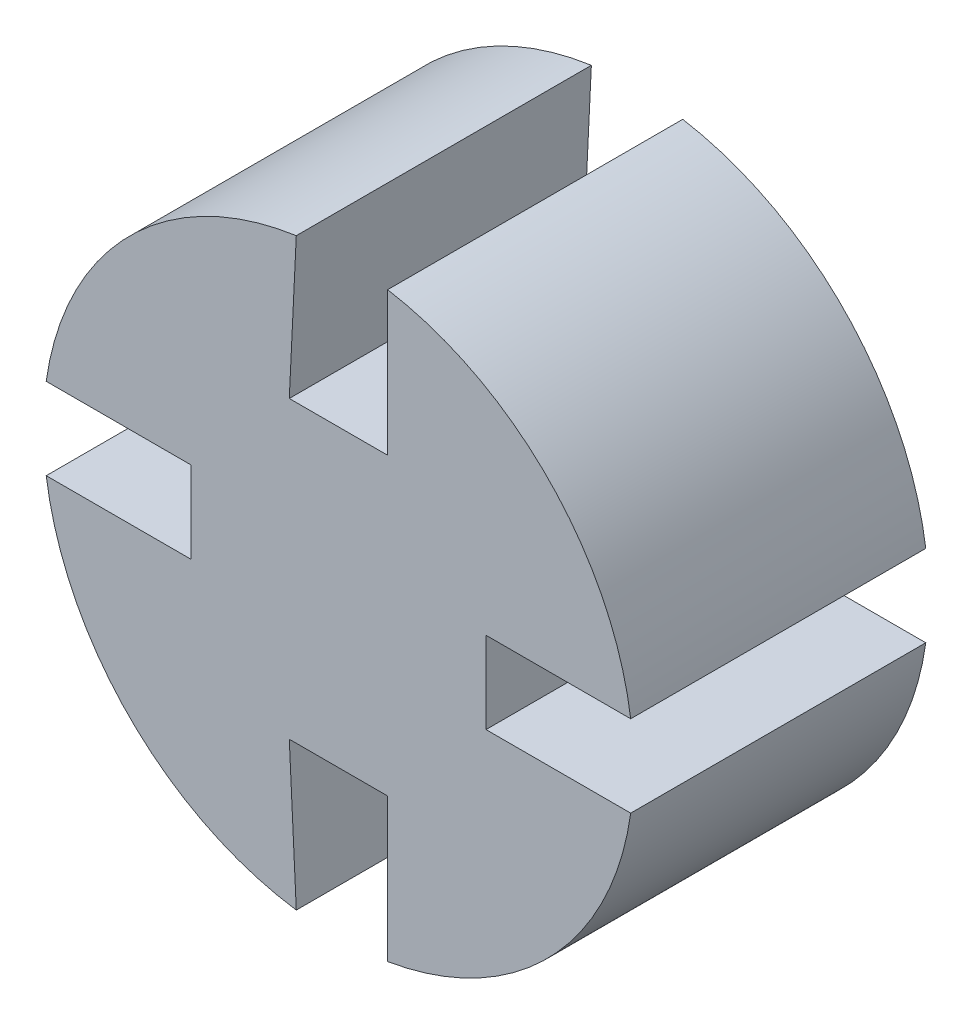
SolidWorks part; units mm, degrees
ref_plane "Alzado" through (0, 0, 0) normal (0, 0, 1) x (1, 0, 0)
ref_plane "Planta" through (0, 0, 0) normal (0, 1, 0) x (1, 0, 0)
ref_plane "Vista lateral" through (0, 0, 0) normal (1, 0, 0) x (0, 0, -1)
sketch "Croquis1" plane through (0, 0, 0) normal (0, 0, 1) x (1, 0, 0)
  line L0 (0, -30) -> (0, 30) construction
  line L1 (-30, 0) -> (30, 0) construction
  line L2 (-8.5752, 59.384) -> (-10, 30)
  line L5 (-10, 30) -> (10, 30)
  line L6 (10, 59.1608) -> (10, 30)
  line L7 (-10, -30) -> (10, -30)
  line L8 (10, -59.1608) -> (10, -30)
  line L9 (-8.5752, -59.384) -> (-10, -30)
  line L10 (59.4223, 8.3061) -> (30, 8.3061)
  line L13 (59.4223, -8.3061) -> (30, -8.3061)
  line L14 (30, 8.3061) -> (30, -8.3061)
  line L15 (-30, 8.3061) -> (-30, -8.3061)
  line L16 (-59.4223, -8.3061) -> (-30, -8.3061)
  line L17 (-59.4223, 8.3061) -> (-30, 8.3061)
  arc A0 (-8.5752, 59.384) -> (-59.4223, 8.3061) centre (0, 0) ccw
  arc A1 (10, -59.1608) -> (59.4223, -8.3061) centre (0, 0) ccw
  arc A2 (59.4223, 8.3061) -> (10, 59.1608) centre (0, 0) ccw
  arc A3 (-59.4223, -8.3061) -> (-8.5752, -59.384) centre (0, 0) ccw
  point P22 (47.8811, 15.9295)
  dimension "D1" = 60
  dimension "D2" = 20
  dimension "D3" = 60
extrude "Saliente-Extruir1" add sketch "Croquis1" along normal blind 60
